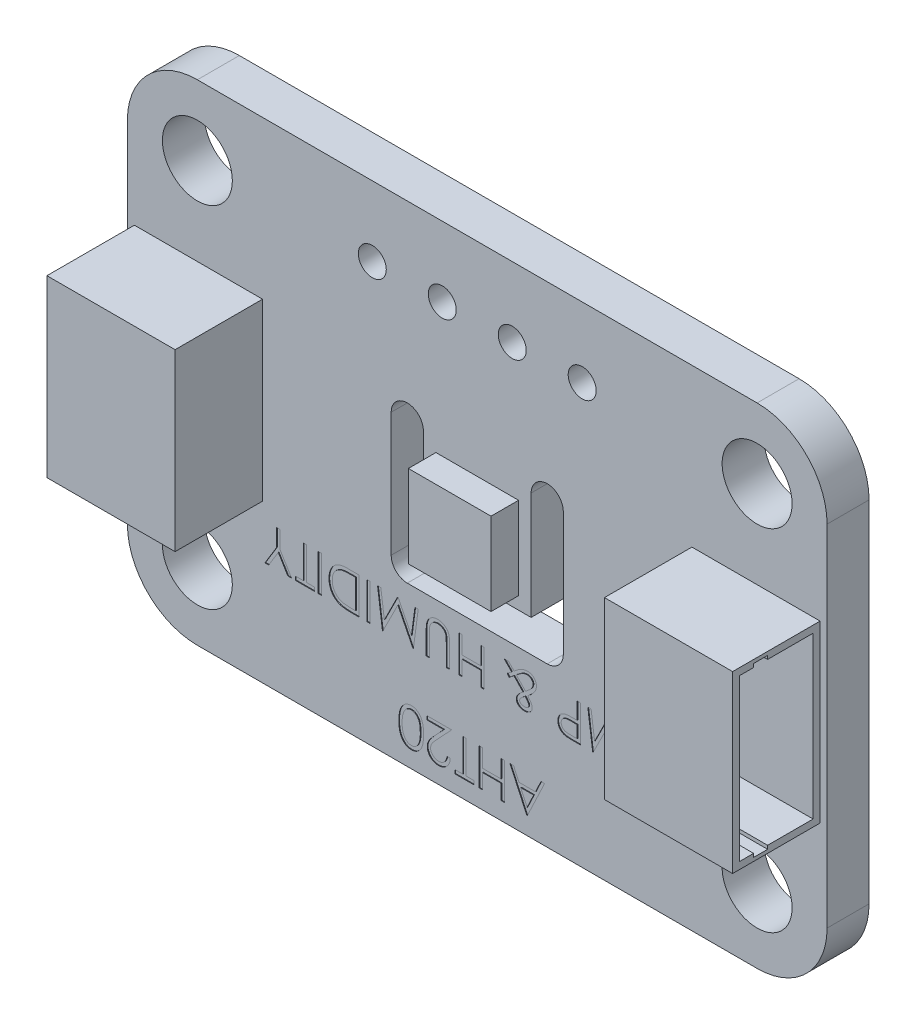
SolidWorks part; units mm, degrees
ref_plane "Front Plane" through (0, 0, 0) normal (0, 0, 1) x (1, 0, 0)
ref_plane "Top Plane" through (0, 0, 0) normal (0, 1, 0) x (1, 0, 0)
ref_plane "Right Plane" through (0, 0, 0) normal (1, 0, 0) x (0, 0, -1)
sketch "Sketch1" plane through (0, 0, 0) normal (0, 0, 1) x (1, 0, 0)
  line L1 (-12.7, -8.89) -> (12.7, -8.89)
  line L2 (-12.7, -8.89) -> (-12.7, 8.89)
  line L3 (-12.7, 8.89) -> (12.7, 8.89)
  line L4 (12.7, -8.89) -> (12.7, 8.89)
  line L5 (-12.7, -8.89) -> (12.7, 8.89) construction
  line L6 (-12.7, 8.89) -> (12.7, -8.89) construction
  point P0 (0, 0)
  dimension "D1" = 25.4
  dimension "D2" = 17.78
extrude "Boss-Extrude1" add sketch "Sketch1" along normal mid plane 1.524
sketch "Sketch2" plane through (0, 0, 0.762) normal (0, 0, 1) x (1, 0, 0)
  line L1 (-12.7, 8.89) -> (-12.7, -8.89) construction
  line L2 (-12.7, -8.89) -> (12.7, -8.89) construction
  circle A0 centre (-10.16, 6.35) radius 1.27
  circle A1 centre (10.16, 6.35) radius 1.27
  circle A2 centre (-10.16, -6.35) radius 1.27
  circle A3 centre (10.16, -6.35) radius 1.27
  circle A5 centre (-3.81, 6.35) radius 0.508
  circle A6 centre (-1.27, 6.35) radius 0.508
  circle A7 centre (1.27, 6.35) radius 0.508
  circle A8 centre (3.81, 6.35) radius 0.508
  point P8 (-1.5476, 6.3986)
  point P9 (0, 0)
  point P22 (-1.5019, 6.35)
  dimension "D5" = 2.54
  dimension "D6" = 3.81
  dimension "D1" = 20.32
  dimension "D2" = 12.7
  dimension "D3" = 2.54
  dimension "D4" = 2.54
  dimension "D10" = 2.54
  dimension "D11" = 2.54
  dimension "D12" = 2.54
extrude "Cut-Extrude1" cut sketch "Sketch2" against normal through all
sketch "Sketch6" plane through (0, 0, 0.762) normal (0, 0, 1) x (1, 0, 0)
  line L1 (-12.446, 3.175) -> (-7.794, 3.175)
  line L2 (-12.446, 3.175) -> (-12.446, -3.175)
  line L3 (-12.446, -3.175) -> (-7.794, -3.175)
  line L4 (-7.794, 3.175) -> (-7.794, -3.175)
  line L5 (7.794, 3.175) -> (12.446, 3.175)
  line L6 (7.794, 3.175) -> (7.794, -3.175)
  line L7 (7.794, -3.175) -> (12.446, -3.175)
  line L8 (12.446, 3.175) -> (12.446, -3.175)
  line L10 (-12.7, 8.89) -> (-12.7, -8.89) construction
  line L11 (12.7, -8.89) -> (12.7, 8.89) construction
  line L12 (-12.7, -8.89) -> (12.7, -8.89) construction
  dimension "D1" = 6.35
  dimension "D2" = 4.652
  dimension "D3" = 4.652
  dimension "D4" = 0.254
  dimension "D5" = 0.254
  dimension "D6" = 5.715
extrude "Boss-Extrude4" add sketch "Sketch6" along normal blind 3.175
sketch "Sketch7" plane through (-12.446, 0, 0) normal (-1, 0, 0) x (0, 0, 1)
  line L0 (3.937, 3.175) -> (0.762, 3.175) construction
  line L1 (1.016, -2.921) -> (2.667, -2.921)
  line L2 (1.016, -2.921) -> (1.016, 2.921)
  line L3 (1.016, 2.921) -> (2.667, 2.921)
  line L4 (3.683, -2.921) -> (3.683, 2.921)
  line L5 (1.016, -2.921) -> (3.683, 2.921) construction
  line L6 (1.016, 2.921) -> (3.683, -2.921) construction
  line L7 (3.937, -3.175) -> (0.762, -3.175) construction
  line L8 (3.937, 3.175) -> (3.937, -3.175) construction
  line L9 (0.762, 3.175) -> (0.762, -3.175) construction
  line L10 (3.175, 2.921) -> (3.683, 2.921)
  line L12 (3.175, 2.921) -> (3.175, 3.048)
  line L13 (3.175, 3.048) -> (2.667, 3.048)
  line L14 (2.667, 2.921) -> (2.667, 3.048)
  line L16 (3.175, -2.921) -> (3.175, -3.048)
  line L17 (3.175, -3.048) -> (2.667, -3.048)
  line L18 (2.667, -2.921) -> (2.667, -3.048)
  line L19 (3.175, -2.921) -> (3.683, -2.921)
  point P0 (2.3495, 0)
  dimension "D1" = 0.254
  dimension "D2" = 0.254
  dimension "D3" = 0.254
  dimension "D4" = 0.254
  dimension "D5" = 0.508
  dimension "D6" = 0.508
  dimension "D7" = 0.127
extrude "Cut-Extrude2" cut sketch "Sketch7" against normal blind 3.175
mirror "Mirror1" about plane through (0, 0, 0) normal (1, 0, 0) of "Cut-Extrude2"
sketch "Sketch8" plane through (0, 0, 0.762) normal (0, 0, 1) x (1, 0, 0)
  line L0 (-3.1242, 1.9558) -> (-3.1242, -2.54)
  line L1 (-2.54, -3.1242) -> (2.54, -3.1242)
  line L2 (3.1242, -2.54) -> (3.1242, 1.9558)
  line L4 (1.9558, 1.9558) -> (1.9558, -1.9558)
  line L5 (1.9558, -1.9558) -> (-1.9558, -1.9558)
  line L6 (-1.9558, -1.9558) -> (-1.9558, 1.9558)
  arc A0 (-1.9558, 1.9558) -> (-3.1242, 1.9558) centre (-2.54, 1.9558) ccw
  arc A1 (3.1242, 1.9558) -> (1.9558, 1.9558) centre (2.54, 1.9558) ccw
  arc A2 (2.54, -3.1242) -> (3.1242, -2.54) centre (2.54, -2.54) ccw
  arc A3 (-2.54, -3.1242) -> (-3.1242, -2.54) centre (-2.54, -2.54) cw
  point P9 (0, -1.9558)
  point P11 (0, 0)
  point P17 (0, 0)
  point P18 (-1.9558, 0)
  dimension "D4" = 0.5842
  dimension "D6" = 5.08
  dimension "D1" = 1.1684
  dimension "D2" = 1.1684
  dimension "D3" = 1.1684
  dimension "D5" = 6.2484
extrude "Cut-Extrude3" cut sketch "Sketch8" against normal through all
fillet "Fillet1" radius 2.54 4 edges at (12.7, -8.89, 0) (-12.7, -8.89, 0) (-12.7, 8.89, 0) (12.7, 8.89, 0)
sketch "Sketch9" plane through (0, 0, 0.762) normal (0, 0, 1) x (1, 0, 0)
  line L1 (-1.5, -1.5) -> (1.5, -1.5)
  line L2 (-1.5, -1.5) -> (-1.5, 1.5)
  line L3 (-1.5, 1.5) -> (1.5, 1.5)
  line L4 (1.5, -1.5) -> (1.5, 1.5)
  line L5 (-1.5, -1.5) -> (1.5, 1.5) construction
  line L6 (-1.5, 1.5) -> (1.5, -1.5) construction
  point P0 (0, 0)
  dimension "D1" = 3
  dimension "D2" = 3
extrude "Boss-Extrude5" add sketch "Sketch9" along normal blind 1
sketch "Sketch10" plane through (0, 0, 0.762) normal (0, 0, 1) x (1, 0, 0)
  line L0 (7.4788, -6.9342) -> (-7.88, -6.9342) construction
  line L1 (-2.54, -3.1242) -> (2.54, -3.1242) construction
  text T0 "AHT20\r\nTEMP & HUMIDITY" font "Century Gothic" height in points 5
  point P2 (7.4788, -5.8893)
  dimension "D1" = 3.81
extrude "Cut-Extrude4" cut sketch "Sketch10" against normal blind 0.0254
